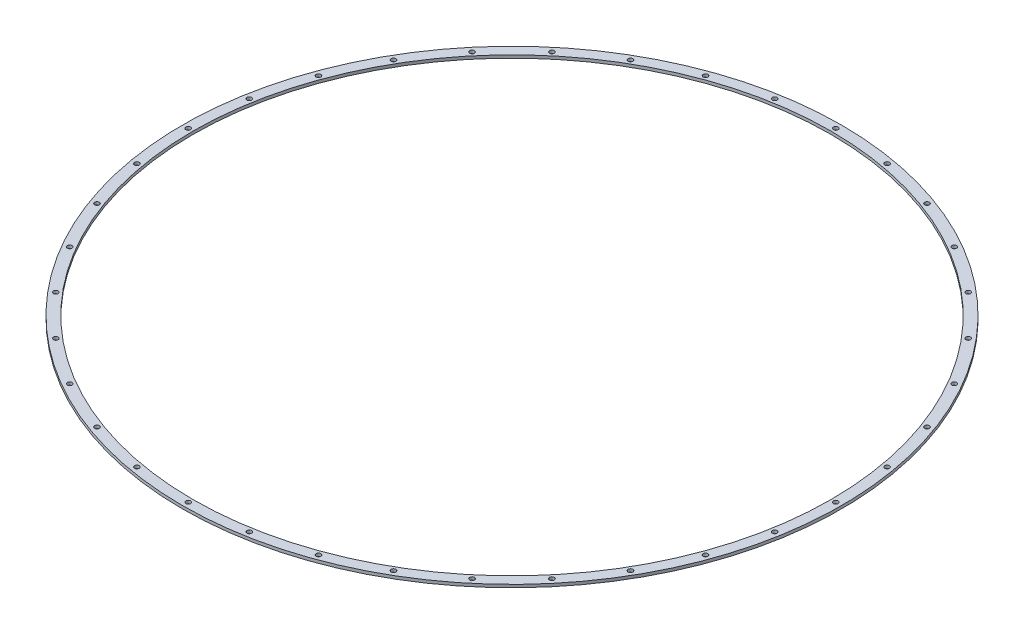
SolidWorks part; units mm, degrees
material "6061-T6 AL"
ref_plane "Front" through (0, 0, 0) normal (0, 0, 1) x (1, 0, 0)
ref_plane "Top" through (0, 0, 0) normal (0, 1, 0) x (1, 0, 0)
ref_plane "Right" through (0, 0, 0) normal (1, 0, 0) x (0, 0, -1)
sketch "Sketch1" plane through (0, 0, 0) normal (0, 1, 0) x (1, 0, 0)
  circle A0 centre (0, 0) radius 692.22
  circle A1 centre (0, 0) radius 715
  dimension "D1" = 1430
  dimension "D2" = 22.78
extrude "Boss-Extrude1" add sketch "Sketch1" along normal blind 6.35
hole_wizard "3/8 Clearance Hole1" positions "Sketch3" profile "Sketch2" hole size "3/8" standard "ANSI Inch" end condition through all
sketch "Sketch3" plane through (0, 6.35, 0) normal (0, 1, 0) x (1, 0, 0)
  circle A1 centre (0, 0) radius 715 construction
  point P0 (0, -702.5)
  dimension "D1" = 702.5
  dimension "D2" = 12.5
sketch "Sketch2" plane through (0, 6.35, 702.5) normal (1, 0, 0) x (0, 0, 1)
  line L0 (0, 0) -> (0, 6.35)
  line L1 (0, 6.35) -> (5.1587, 6.35)
  line L2 (5.1587, 6.35) -> (5.1587, 0)
  line L5 (5.1587, 0) -> (0, 0)
  line L11 (0, -6.35) -> (0, 107.95) construction
  dimension "Thru Hole Dia." = 10.3175
  dimension "Thru Hole Depth" = 6.35
pattern_circular "CirPattern1" count 36 over 360 about axis through (0, 0, 0) along (0, 1, 0) of "3/8 Clearance Hole1"
chamfer "Chamfer1" [suppressed] distance 3.175 angle 45
